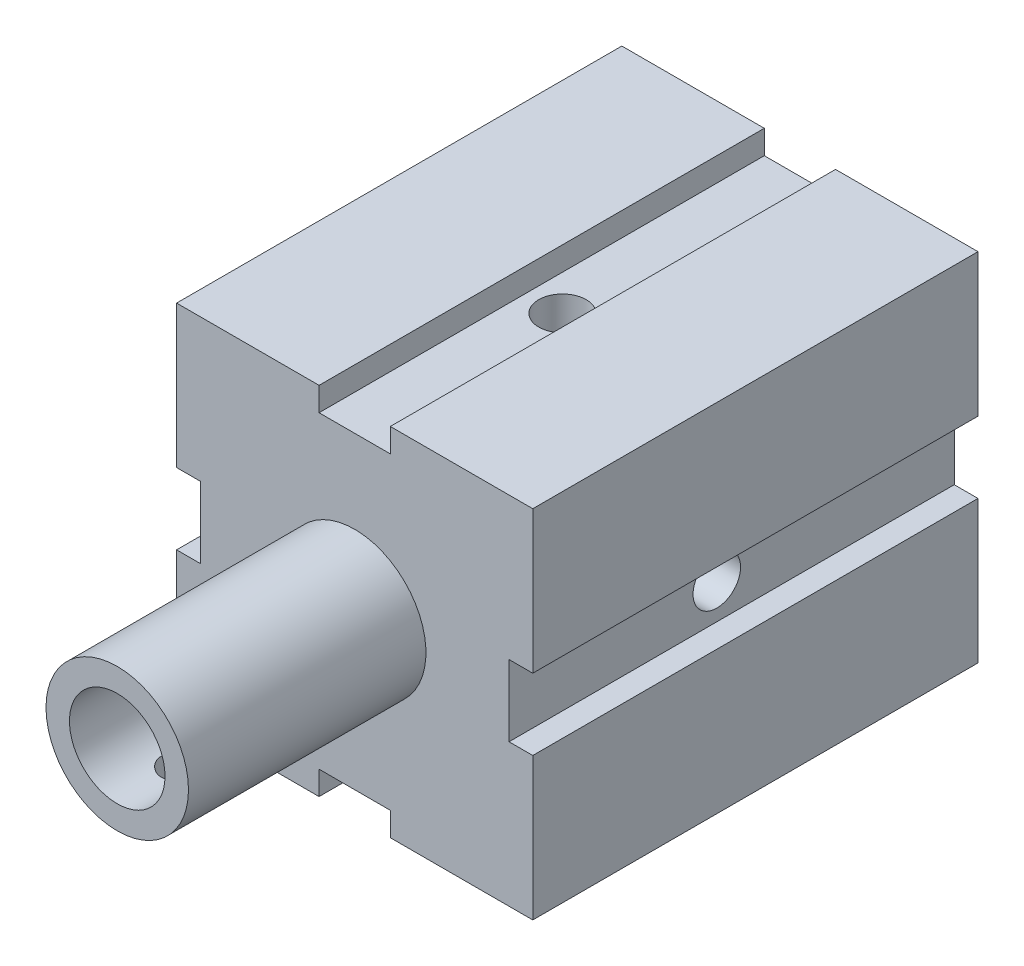
SolidWorks part; units mm, degrees
ref_plane "Front Plane" through (0, 0, 0) normal (0, 0, 1) x (1, 0, 0)
ref_plane "Top Plane" through (0, 0, 0) normal (0, 1, 0) x (1, 0, 0)
ref_plane "Right Plane" through (0, 0, 0) normal (1, 0, 0) x (0, 0, -1)
sketch "Sketch1" plane through (0, 0, 0) normal (0, 0, 1) x (1, 0, 0)
  line L1 (302.8649, 107.5498) -> (332.8649, 107.5498)
  line L2 (302.8649, 107.5498) -> (302.8649, 77.5498)
  line L3 (302.8649, 77.5498) -> (332.8649, 77.5498)
  line L4 (332.8649, 107.5498) -> (332.8649, 77.5498)
  dimension "D1" = 30
  dimension "D2" = 30
extrude "Boss-Extrude1" add sketch "Sketch1" along normal blind 37.5 contours L2 L3 L4 L1
sketch "Sketch2" plane through (0, 0, 37.5) normal (0, 0, 1) x (1, 0, 0)
  line L0 (317.8649, 77.5498) -> (317.8649, 107.5498) construction
  line L1 (302.8649, 77.5498) -> (332.8649, 77.5498) construction
  line L2 (302.8649, 107.5498) -> (332.8649, 107.5498) construction
  circle A0 centre (317.8649, 92.5498) radius 6
  circle A1 centre (317.8649, 92.5498) radius 4.025
extrude "Boss-Extrude2" add sketch "Sketch2" along normal blind 20
sketch "Sketch3" plane through (0, 0, 37.5) normal (0, 0, 1) x (1, 0, 0)
  circle A0 centre (317.8649, 92.5498) radius 4.025
extrude "Cut-Extrude1" cut sketch "Sketch3" against normal blind 10
sketch "Sketch4" plane through (0, 77.5498, 0) normal (0, -1, 0) x (1, 0, 0)
  line L0 (302.8649, 0) -> (332.8649, 0) construction
  line L1 (314.8649, -37.5) -> (320.8649, -37.5)
  line L2 (314.8649, -37.5) -> (314.8649, 37.5)
  line L3 (314.8649, 37.5) -> (320.8649, 37.5)
  line L4 (320.8649, -37.5) -> (320.8649, 37.5)
  line L5 (314.8649, -37.5) -> (320.8649, 37.5) construction
  line L6 (314.8649, 37.5) -> (320.8649, -37.5) construction
  line L7 (302.8649, 37.5) -> (332.8649, 37.5) construction
  point P0 (317.8649, 0)
  dimension "D1" = 6
extrude "Cut-Extrude2" cut sketch "Sketch4" against normal blind 2
pattern_circular "CirPattern1" count 4 over 360 about axis through (317.8649, 92.5498, 0) along (0, 0, 1) of "Cut-Extrude2"
sketch "Sketch5" plane through (330.8649, 0, 0) normal (1, 0, 0) x (0, 0, -1)
  line L0 (-37.5, 92.5498) -> (0, 92.5498) construction
  line L1 (-37.5, 95.5498) -> (-37.5, 89.5498) construction
  line L2 (0, 89.5498) -> (0, 95.5498) construction
  circle A0 centre (-20, 92.5498) radius 2
  dimension "D1" = 20
extrude "Cut-Extrude3" cut sketch "Sketch5" against normal through all
sketch "Sketch6" plane through (0, 79.5498, 0) normal (0, -1, 0) x (1, 0, 0)
  line L0 (317.8649, 37.5) -> (317.8649, 0) construction
  line L1 (320.8649, 37.5) -> (314.8649, 37.5) construction
  line L2 (314.8649, 0) -> (320.8649, 0) construction
  circle A0 centre (317.8649, 20) radius 2
  dimension "D1" = 20
extrude "Cut-Extrude4" cut sketch "Sketch6" against normal through all
hole_wizard "M3x0.5 Tapped Hole1" positions "3DSketch1" profile "Sketch7" tap size "M3x0.5" standard "ANSI Metric"
sketch3d "3DSketch1"
  point P0 (317.712, 86.5517, 43.6128)
  point P2 (317.6684, 86.553, 52.4548)
sketch "Sketch7" plane through (317.712, 86.5517, 43.6128) normal (0, 0, 1) x (0.9997, -0.0255, 0)
  line L0 (0, 0) -> (0, 1.975)
  line L1 (0, 1.975) -> (1.25, 1.975)
  line L2 (1.25, 1.975) -> (1.25, 0)
  line L5 (1.25, 0) -> (0, 0)
  line L11 (0, -6.35) -> (0, 107.95) construction
  dimension "Thru Tap Drill Dia." = 2.5
  dimension "Thru Tap Drill Depth" = 1.975
cosmetic thread "Hole Thread1" parameters "D2"=3
cosmetic thread "Hole Thread2" parameters "D2"=3
